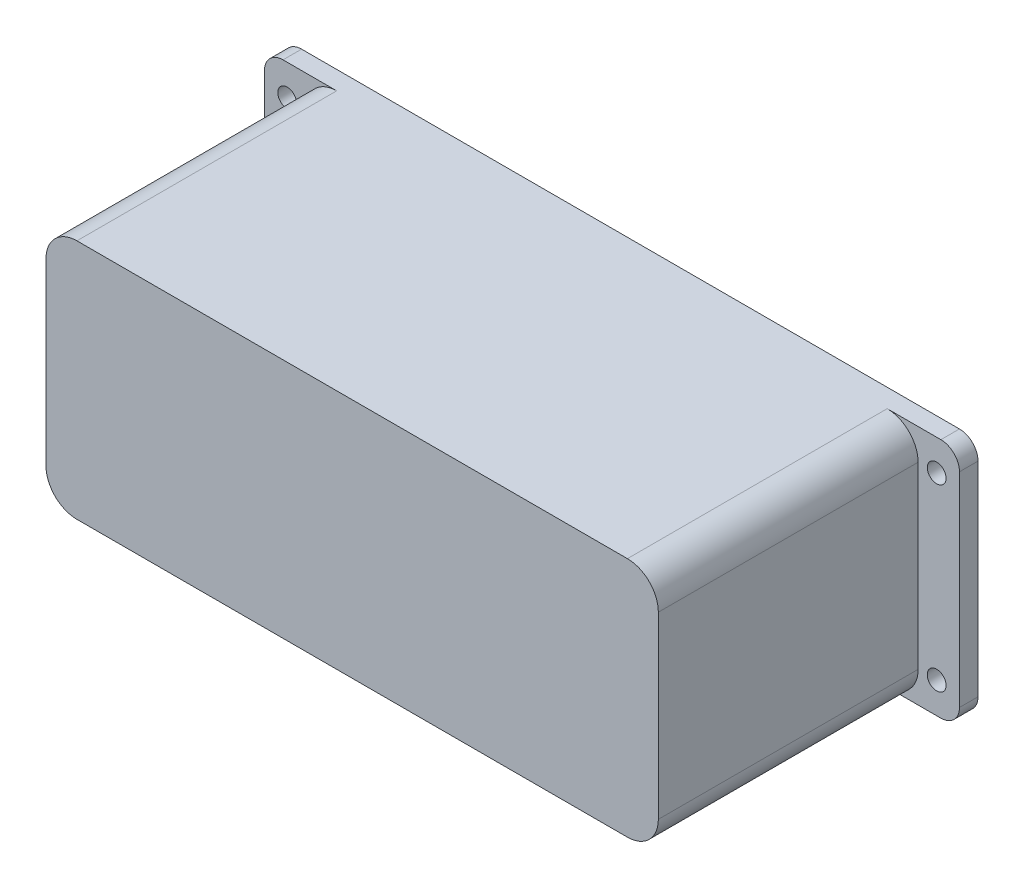
SolidWorks part; units mm, degrees
material "ABS"
ref_plane "前视基准面" through (0, 0, 0) normal (0, 0, 1) x (1, 0, 0)
ref_plane "上视基准面" through (0, 0, 0) normal (0, 1, 0) x (1, 0, 0)
ref_plane "右视基准面" through (0, 0, 0) normal (1, 0, 0) x (0, 0, -1)
other "Configuration Table"
sketch "草图1" plane through (0, 0, 0) normal (0, 0, 1) x (1, 0, 0)
  line L1 (-79.5, -19.5) -> (79.5, -19.5)
  line L2 (-79.5, -19.5) -> (-79.5, 19.5)
  line L3 (-79.5, 19.5) -> (79.5, 19.5)
  line L4 (79.5, -19.5) -> (79.5, 19.5)
  line L5 (-79.5, -19.5) -> (79.5, 19.5) construction
  line L6 (-79.5, 19.5) -> (79.5, -19.5) construction
  point P0 (0, 0)
  dimension "D1" = 159
  dimension "D2" = 39
extrude "凸台-拉伸1" add sketch "草图1" along normal blind 2
fillet "圆角1" radius 3 4 edges at (-79.5, -19.5, 1) (-79.5, 19.5, 1) (79.5, -19.5, 1) (79.5, 19.5, 1)
sketch "草图2" plane through (0, 0, 2) normal (0, 0, 1) x (1, 0, 0)
  line L0 (79.5, -16.5) -> (79.5, 16.5) construction
  line L1 (73, -7.5) -> (86, -7.5)
  line L2 (73, -7.5) -> (73, 7.5)
  line L3 (73, 7.5) -> (86, 7.5)
  line L4 (86, -7.5) -> (86, 7.5)
  line L5 (73, -7.5) -> (86, 7.5) construction
  line L6 (73, 7.5) -> (86, -7.5) construction
  line L8 (-52.5, -14.5) -> (52.5, -14.5) construction
  line L9 (-52.5, -14.5) -> (-52.5, 14.5) construction
  line L10 (-52.5, 14.5) -> (52.5, 14.5) construction
  line L11 (52.5, -14.5) -> (52.5, 14.5) construction
  line L12 (-52.5, -14.5) -> (52.5, 14.5) construction
  line L13 (-52.5, 14.5) -> (52.5, -14.5) construction
  circle A0 centre (52.5, 14.5) radius 1.52
  circle A1 centre (-52.5, 14.5) radius 1.52
  circle A2 centre (-52.5, -14.5) radius 1.52
  circle A3 centre (52.5, -14.5) radius 1.52
  point P0 (79.5, 0)
  point P7 (0, 0)
  dimension "D5" = 3.04
  dimension "D1" = 105
  dimension "D2" = 29
  dimension "D3" = 13
  dimension "D4" = 15
extrude "切除-拉伸1" cut sketch "草图2" against normal blind 55
ref_plane "基准面1" through (0, 0, 4) normal (0, 0, 1) x (1, 0, 0)
sketch "草图4" plane through (0, 0, 4) normal (0, 0, 1) x (1, 0, 0)
  line L8 (79.5, -16.5) -> (79.5, -7.5)
  line L9 (79.5, -7.5) -> (73, -7.5)
  line L10 (73, -7.5) -> (73, 7.5)
  line L11 (73, 7.5) -> (79.5, 7.5)
  line L12 (79.5, 7.5) -> (79.5, 16.5)
  line L13 (76.5, 19.5) -> (-76.5, 19.5)
  line L14 (-79.5, 16.5) -> (-79.5, -16.5)
  line L15 (-76.5, -19.5) -> (76.5, -19.5)
  line L16 (79.5, -16.5) -> (79.5, -7.5)
  line L17 (79.5, -7.5) -> (73, -7.5)
  line L18 (73, -7.5) -> (73, 7.5)
  line L19 (73, 7.5) -> (79.5, 7.5)
  line L20 (79.5, 7.5) -> (79.5, 16.5)
  line L21 (76.5, 19.5) -> (-76.5, 19.5)
  line L22 (-79.5, 16.5) -> (-79.5, -16.5)
  line L23 (-76.5, -19.5) -> (76.5, -19.5)
  arc A4 (79.5, 16.5) -> (76.5, 19.5) centre (76.5, 16.5) ccw
  arc A5 (-76.5, 19.5) -> (-79.5, 16.5) centre (-76.5, 16.5) ccw
  arc A6 (-79.5, -16.5) -> (-76.5, -19.5) centre (-76.5, -16.5) ccw
  arc A7 (76.5, -19.5) -> (79.5, -16.5) centre (76.5, -16.5) ccw
  arc A8 (79.5, 16.5) -> (76.5, 19.5) centre (76.5, 16.5) ccw
  arc A9 (-76.5, 19.5) -> (-79.5, 16.5) centre (-76.5, 16.5) ccw
  arc A10 (-79.5, -16.5) -> (-76.5, -19.5) centre (-76.5, -16.5) ccw
  arc A11 (76.5, -19.5) -> (79.5, -16.5) centre (76.5, -16.5) ccw
  dimension "D1" = 0
extrude "凸台-拉伸2" add sketch "草图4" along normal blind 3 separate body
sketch "草图5" plane through (0, 0, 7) normal (0, 0, 1) x (1, 0, 0)
  line L0 (76.5, 19.5) -> (-76.5, 19.5) construction
  line L1 (-49.5, -19.5) -> (49.5, -19.5)
  line L2 (-49.5, -19.5) -> (-49.5, 19.5)
  line L3 (-49.5, 19.5) -> (49.5, 19.5)
  line L4 (49.5, -19.5) -> (49.5, 19.5)
  line L5 (-49.5, -19.5) -> (49.5, 19.5) construction
  line L6 (-49.5, 19.5) -> (49.5, -19.5) construction
  circle A0 centre (52.5, 14.5) radius 1.52 construction
  point P0 (0, 0)
  dimension "D1" = 3
extrude "凸台-拉伸3" add sketch "草图5" along normal blind 44
sketch "草图7" plane through (0, 0, 7) normal (0, 0, 1) x (1, 0, 0)
  circle A0 centre (-52.5, -14.5) radius 1.52 construction
  circle A1 centre (-52.5, 14.5) radius 1.52 construction
  circle A2 centre (52.5, -14.5) radius 1.52 construction
  circle A3 centre (52.5, 14.5) radius 1.52 construction
  circle A4 centre (-52.5, -14.5) radius 1.52
  circle A5 centre (-52.5, 14.5) radius 1.52
  circle A6 centre (52.5, -14.5) radius 1.52
  circle A7 centre (52.5, 14.5) radius 1.52
extrude "切除-拉伸2" cut sketch "草图7" against normal blind 45
fillet "圆角2" radius 5 4 edges at (49.5, 19.5, 29) (-49.5, 19.5, 29) (-49.5, -19.5, 29) (49.5, -19.5, 29)
sketch "草图8" plane through (0, 0, 4) normal (0, 0, -1) x (-1, 0, 0)
  line L8 (-48.18, 14.5) -> (-48.18, -14.5)
  line L9 (44.5, 18.18) -> (-44.5, 18.18)
  line L10 (48.18, -14.5) -> (48.18, 14.5)
  line L11 (-44.5, -18.18) -> (44.5, -18.18)
  line L12 (-48.18, 14.5) -> (-48.18, -14.5)
  line L13 (44.5, 18.18) -> (-44.5, 18.18)
  line L14 (48.18, -14.5) -> (48.18, 14.5)
  line L15 (-44.5, -18.18) -> (44.5, -18.18)
  arc A4 (48.18, 14.5) -> (44.5, 18.18) centre (44.5, 14.5) ccw
  arc A5 (48.18, 14.5) -> (44.5, 18.18) centre (44.5, 14.5) ccw
  arc A6 (44.5, -18.18) -> (48.18, -14.5) centre (44.5, -14.5) ccw
  arc A7 (44.5, -18.18) -> (48.18, -14.5) centre (44.5, -14.5) ccw
  arc A8 (-48.18, -14.5) -> (-44.5, -18.18) centre (-44.5, -14.5) ccw
  arc A9 (-48.18, -14.5) -> (-44.5, -18.18) centre (-44.5, -14.5) ccw
  arc A10 (-44.5, 18.18) -> (-48.18, 14.5) centre (-44.5, 14.5) ccw
  arc A11 (-44.5, 18.18) -> (-48.18, 14.5) centre (-44.5, 14.5) ccw
  dimension "D1" = 1.32
extrude "切除-拉伸4" cut sketch "草图8" against normal blind 43
sketch "草图9" plane through (0, 0, 0) normal (0, 0, -1) x (-1, 0, 0)
  line L0 (-73, -7.5) -> (-73, 7.5) construction
  line L1 (-73, 7.5) -> (-68, 7.5)
  line L2 (-73, 7.5) -> (-73, -7.5)
  line L3 (-73, -7.5) -> (-68, -7.5)
  line L4 (-68, 7.5) -> (-68, -7.5)
  line L5 (-79.5, 7.5) -> (-79.5, 16.5) construction
  line L6 (-79.5, -7.5) -> (-73, -7.5) construction
  dimension "D1" = 11.5
extrude "切除-拉伸5" cut sketch "草图9" against normal blind 6
sketch "草图10" plane through (0, 0, 0) normal (0, 0, -1) x (-1, 0, 0)
  line L1 (-17.5, -23.5) -> (17.5, -23.5) construction
  line L2 (-17.5, -23.5) -> (-17.5, 23.5) construction
  line L3 (-17.5, 23.5) -> (17.5, 23.5) construction
  line L4 (17.5, -23.5) -> (17.5, 23.5) construction
  line L5 (-17.5, -23.5) -> (17.5, 23.5) construction
  line L6 (-17.5, 23.5) -> (17.5, -23.5) construction
  line L7 (-25, -27.5) -> (25, -27.5)
  line L8 (-25, -27.5) -> (-25, 27.5)
  line L9 (-25, 27.5) -> (25, 27.5)
  line L10 (25, -27.5) -> (25, 27.5)
  line L11 (-25, -27.5) -> (25, 27.5) construction
  line L12 (-25, 27.5) -> (25, -27.5) construction
  line L14 (-76.5, 19.5) -> (76.5, 19.5) construction
  circle A0 centre (-17.5, 23.5) radius 2.025
  circle A1 centre (17.5, 23.5) radius 2.025
  circle A2 centre (-17.5, -23.5) radius 2.025
  circle A3 centre (17.5, -23.5) radius 2.025
  point P0 (0, 0)
  point P6 (0, 0)
  dimension "D5" = 4.05
  dimension "D1" = 35
  dimension "D2" = 4
  dimension "D3" = 50
  dimension "D4" = 4
extrude "凸台-拉伸4" add sketch "草图10" against normal up to surface (2 mm away) up to face at (54.02, 14.5, 2)
fillet "圆角3" radius 4 8 edges at (-25, 19.5, 1) (-25, 27.5, 1) (25, 19.5, 1) (25, -19.5, 1) (25, -27.5, 1) (-25, -27.5, 1) (-25, -19.5, 1) (25, 27.5, 1)
sketch "草图11" plane through (0, 0, 51) normal (0, 0, 1) x (1, 0, 0)
  line L4 (44.5, 19.5) -> (-44.5, 19.5)
  line L5 (-49.5, 14.5) -> (-49.5, -14.5)
  line L6 (-44.5, -19.5) -> (44.5, -19.5)
  line L7 (49.5, -14.5) -> (49.5, 14.5)
  line L8 (44.5, 19.5) -> (-44.5, 19.5)
  line L9 (-49.5, 14.5) -> (-49.5, -14.5)
  line L10 (-44.5, -19.5) -> (44.5, -19.5)
  line L11 (49.5, -14.5) -> (49.5, 14.5)
  arc A4 (-44.5, 19.5) -> (-49.5, 14.5) centre (-44.5, 14.5) ccw
  arc A5 (-49.5, -14.5) -> (-44.5, -19.5) centre (-44.5, -14.5) ccw
  arc A6 (44.5, -19.5) -> (49.5, -14.5) centre (44.5, -14.5) ccw
  arc A7 (49.5, 14.5) -> (44.5, 19.5) centre (44.5, 14.5) ccw
  arc A8 (-44.5, 19.5) -> (-49.5, 14.5) centre (-44.5, 14.5) ccw
  arc A9 (-49.5, -14.5) -> (-44.5, -19.5) centre (-44.5, -14.5) ccw
  arc A10 (44.5, -19.5) -> (49.5, -14.5) centre (44.5, -14.5) ccw
  arc A11 (49.5, 14.5) -> (44.5, 19.5) centre (44.5, 14.5) ccw
  dimension "D1" = 0
extrude "切除-拉伸6" cut sketch "草图11" against normal blind 2
sketch "草图12" plane through (0, 0, 7) normal (0, 0, 1) x (1, 0, 0)
  line L0 (-29, 19.5) -> (29, 19.5)
  line L1 (-29, -19.5) -> (29, -19.5)
  line L12 (21, 27.5) -> (-21, 27.5)
  line L13 (-29, 19.5) -> (-76.5, 19.5)
  line L14 (-79.5, 16.5) -> (-79.5, -16.5)
  line L15 (-76.5, -19.5) -> (-29, -19.5)
  line L16 (-21, -27.5) -> (21, -27.5)
  line L17 (29, -19.5) -> (76.5, -19.5)
  line L18 (79.5, -16.5) -> (79.5, -7.5)
  line L19 (79.5, -7.5) -> (68, -7.5)
  line L20 (68, -7.5) -> (68, 7.5)
  line L21 (68, 7.5) -> (79.5, 7.5)
  line L22 (79.5, 7.5) -> (79.5, 16.5)
  line L23 (76.5, 19.5) -> (29, 19.5)
  line L24 (21, 27.5) -> (-21, 27.5)
  line L28 (-21, -27.5) -> (21, -27.5)
  arc A12 (-21, 27.5) -> (-25, 23.5) centre (-21, 23.5) ccw
  arc A13 (-29, 19.5) -> (-25, 23.5) centre (-29, 23.5) ccw
  arc A14 (-76.5, 19.5) -> (-79.5, 16.5) centre (-76.5, 16.5) ccw
  arc A15 (-79.5, -16.5) -> (-76.5, -19.5) centre (-76.5, -16.5) ccw
  arc A16 (-25, -23.5) -> (-29, -19.5) centre (-29, -23.5) ccw
  arc A17 (-25, -23.5) -> (-21, -27.5) centre (-21, -23.5) ccw
  arc A18 (21, -27.5) -> (25, -23.5) centre (21, -23.5) ccw
  arc A19 (29, -19.5) -> (25, -23.5) centre (29, -23.5) ccw
  arc A20 (76.5, -19.5) -> (79.5, -16.5) centre (76.5, -16.5) ccw
  arc A21 (79.5, 16.5) -> (76.5, 19.5) centre (76.5, 16.5) ccw
  arc A22 (25, 23.5) -> (29, 19.5) centre (29, 23.5) ccw
  arc A23 (25, 23.5) -> (21, 27.5) centre (21, 23.5) ccw
  arc A24 (-21, 27.5) -> (-25, 23.5) centre (-21, 23.5) ccw
  arc A25 (-29, 19.5) -> (-25, 23.5) centre (-29, 23.5) ccw
  arc A28 (-25, -23.5) -> (-29, -19.5) centre (-29, -23.5) ccw
  arc A29 (-25, -23.5) -> (-21, -27.5) centre (-21, -23.5) ccw
  arc A30 (21, -27.5) -> (25, -23.5) centre (21, -23.5) ccw
  arc A31 (29, -19.5) -> (25, -23.5) centre (29, -23.5) ccw
  arc A32 (76.5, -19.5) -> (79.5, -16.5) centre (76.5, -16.5) ccw
  arc A34 (25, 23.5) -> (29, 19.5) centre (29, 23.5) ccw
  arc A35 (25, 23.5) -> (21, 27.5) centre (21, 23.5) ccw
  dimension "D1" = 0
extrude "切除-拉伸7" cut sketch "草图12" against normal blind 32 contours A31 L1 A28 A29 L28 A30 | A34 A35 L24 A24 A25 L0
sketch "草图13" plane through (0, 0, 7) normal (0, 0, 1) x (1, 0, 0)
  line L1 (74, -14.5) -> (-74, -14.5) construction
  line L2 (74, -14.5) -> (74, 14.5) construction
  line L3 (74, 14.5) -> (-74, 14.5) construction
  line L4 (-74, -14.5) -> (-74, 14.5) construction
  line L5 (74, -14.5) -> (-74, 14.5) construction
  line L6 (74, 14.5) -> (-74, -14.5) construction
  circle A0 centre (-74, 14.5) radius 2.025
  circle A1 centre (-74, -14.5) radius 2.025
  circle A2 centre (74, -14.5) radius 2.025
  circle A3 centre (74, 14.5) radius 2.025
  point P0 (0, 0)
  dimension "D2" = 29
  dimension "D3" = 4.05
  dimension "D1" = 148
extrude "切除-拉伸8" cut sketch "草图13" against normal blind 32
sketch "草图14" plane through (0, 0, 7) normal (0, 0, 1) x (1, 0, 0)
  line L0 (49.5, -14.5) -> (49.5, 14.5) construction
  line L1 (73, 7.5) -> (49.5, 7.5)
  line L2 (73, 7.5) -> (73, -7.5)
  line L3 (73, -7.5) -> (49.5, -7.5)
  line L4 (49.5, 7.5) -> (49.5, -7.5)
extrude "切除-拉伸9" cut sketch "草图14" against normal blind 3
sketch "草图15" plane through (0, 0, 0) normal (0, 0, -1) x (-1, 0, 0)
  line L0 (-68, -7.5) -> (-68, 7.5) construction
  line L1 (-68, 7.5) -> (-43, 7.5)
  line L2 (-68, 7.5) -> (-68, -7.5)
  line L3 (-68, -7.5) -> (-43, -7.5)
  line L4 (-43, 7.5) -> (-43, -7.5)
  dimension "D1" = 25
extrude "切除-拉伸10" cut sketch "草图15" against normal up to surface (7 mm away)
fillet "圆角4" radius 3 2 edges at (79.5, -7.5, 5.5) (79.5, 7.5, 5.5)
fillet "圆角5" radius 3 2 edges at (79.5, -7.5, 1) (79.5, 7.5, 1)
sketch "草图16" plane through (0, 0, 4) normal (0, 0, -1) x (-1, 0, 0)
  line L0 (-76.5, -7.5) -> (-48.18, -7.5) construction
  line L1 (-48.18, 7.5) -> (-56.18, 7.5)
  line L2 (-48.18, 7.5) -> (-48.18, -7.5)
  line L3 (-48.18, -7.5) -> (-56.18, -7.5)
  line L4 (-56.18, 7.5) -> (-56.18, -7.5)
  dimension "D1" = 8
extrude "凸台-拉伸5" add sketch "草图16" against normal up to surface (3 mm away)
sketch "草图17" plane through (0, 0, 7) normal (0, 0, 1) x (1, 0, 0)
  line L0 (-44.5, 19.5) -> (-76.5, 19.5) construction
  line L1 (-56.18, 19.5) -> (-79.5, 19.5)
  line L2 (-56.18, 19.5) -> (-56.18, -19.5)
  line L3 (-56.18, -19.5) -> (-79.5, -19.5)
  line L4 (-79.5, 19.5) -> (-79.5, -19.5)
  line L5 (-76.5, -19.5) -> (-44.5, -19.5) construction
  line L6 (-79.5, 16.5) -> (-79.5, -16.5) construction
  line L7 (0, 0) -> (0, -50000) construction
  line L8 (79.5, 19.5) -> (79.5, -19.5)
  line L9 (56.18, -19.5) -> (79.5, -19.5)
  line L10 (56.18, 19.5) -> (56.18, -19.5)
  line L11 (56.18, 19.5) -> (79.5, 19.5)
  line L12 (56.18, 7.5) -> (56.18, -7.5) construction
extrude "切除-拉伸11" cut sketch "草图17" against normal up to surface (5 mm away)
fillet "圆角6" radius 3 4 edges at (56.18, -19.5, 5.5) (56.18, 19.5, 5.5) (-56.18, 19.5, 5.5) (-56.18, -19.5, 5.5)
sketch "草图18" plane through (0, 0, 0) normal (0, 0, -1) x (-1, 0, 0)
  line L8 (-43, -7.5) -> (-76.5, -7.5)
  line L9 (-79.5, -10.5) -> (-79.5, -16.5)
  line L10 (-76.5, -19.5) -> (76.5, -19.5)
  line L11 (79.5, -16.5) -> (79.5, 16.5)
  line L12 (76.5, 19.5) -> (-76.5, 19.5)
  line L13 (-79.5, 16.5) -> (-79.5, 10.5)
  line L14 (-76.5, 7.5) -> (-43, 7.5)
  line L15 (-43, 7.5) -> (-43, -7.5)
  line L16 (-43, -7.5) -> (-76.5, -7.5)
  line L17 (-79.5, -10.5) -> (-79.5, -16.5)
  line L18 (-76.5, -19.5) -> (76.5, -19.5)
  line L19 (79.5, -16.5) -> (79.5, 16.5)
  line L20 (76.5, 19.5) -> (-76.5, 19.5)
  line L21 (-79.5, 16.5) -> (-79.5, 10.5)
  line L22 (-76.5, 7.5) -> (-43, 7.5)
  line L23 (-43, 7.5) -> (-43, -7.5)
  arc A6 (-76.5, -7.5) -> (-79.5, -10.5) centre (-76.5, -10.5) ccw
  arc A7 (-79.5, -16.5) -> (-76.5, -19.5) centre (-76.5, -16.5) ccw
  arc A8 (76.5, -19.5) -> (79.5, -16.5) centre (76.5, -16.5) ccw
  arc A9 (79.5, 16.5) -> (76.5, 19.5) centre (76.5, 16.5) ccw
  arc A10 (-76.5, 19.5) -> (-79.5, 16.5) centre (-76.5, 16.5) ccw
  arc A11 (-79.5, 10.5) -> (-76.5, 7.5) centre (-76.5, 10.5) ccw
  arc A12 (-76.5, -7.5) -> (-79.5, -10.5) centre (-76.5, -10.5) ccw
  arc A13 (-79.5, -16.5) -> (-76.5, -19.5) centre (-76.5, -16.5) ccw
  arc A14 (76.5, -19.5) -> (79.5, -16.5) centre (76.5, -16.5) ccw
  arc A15 (79.5, 16.5) -> (76.5, 19.5) centre (76.5, 16.5) ccw
  arc A16 (-76.5, 19.5) -> (-79.5, 16.5) centre (-76.5, 16.5) ccw
  arc A17 (-79.5, 10.5) -> (-76.5, 7.5) centre (-76.5, 10.5) ccw
  dimension "D1" = 0
extrude "切除-拉伸12" cut sketch "草图18" against normal up to surface (2 mm away)
